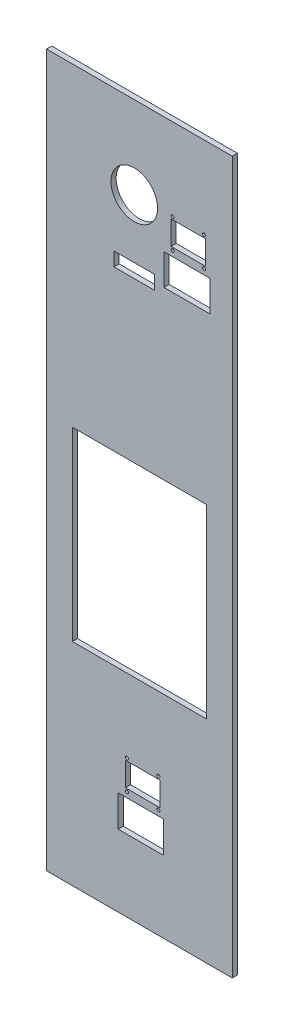
SolidWorks part; units mm, degrees
ref_plane "Plan de face" through (0, 0, 0) normal (0, 0, 1) x (1, 0, 0)
ref_plane "Plan de dessus" through (0, 0, 0) normal (0, 1, 0) x (1, 0, 0)
ref_plane "Plan de droite" through (0, 0, 0) normal (1, 0, 0) x (0, 0, -1)
sketch "Esquisse1" plane through (0, 0, 0) normal (0, 0, 1) x (1, 0, 0)
  line L1 (-90, 395) -> (90, 395)
  line L2 (-90, 395) -> (-90, -395)
  line L3 (-90, -395) -> (90, -395)
  line L4 (90, 395) -> (90, -395)
  line L5 (-90, 395) -> (90, -395) construction
  line L6 (-90, -395) -> (90, 395) construction
  point P0 (0, 0)
  dimension "D1" = 790
  dimension "D2" = 180
extrude "Boss.-Extru.1" add sketch "Esquisse1" along normal blind 5
sketch "Esquisse2" plane through (0, 0, 5) normal (0, 0, 1) x (1, 0, 0)
  line L1 (-65, 90) -> (65, 90)
  line L2 (-65, 90) -> (-65, -90)
  line L3 (-65, -90) -> (65, -90)
  line L4 (65, 90) -> (65, -90)
  line L5 (-65, 90) -> (65, -90) construction
  line L6 (-65, -90) -> (65, 90) construction
  point P0 (0, 0)
  dimension "D1" = 130
  dimension "D2" = 180
extrude "Enlèv. mat.-Extru.1" cut sketch "Esquisse2" against normal through all
sketch "Esquisse3" plane through (0, 0, 5) normal (0, 0, 1) x (1, 0, 0)
  line L0 (-90, -295) -> (90, -295)
  line L1 (-90, 395) -> (-90, -395) construction
  line L2 (90, -395) -> (90, 395) construction
  line L7 (90, -395) -> (90, 395)
  line L8 (90, 395) -> (-90, 395)
  line L9 (-90, 395) -> (-90, -395)
  line L10 (-90, -395) -> (90, -395)
  line L11 (90, -395) -> (90, -295)
  line L13 (-90, -295) -> (-90, -395)
  line L14 (-90, -395) -> (90, -395)
  dimension "D2" = 100
  dimension "D1" = 0
extrude "Enlèv. mat.-Extru.2" cut sketch "Esquisse3" against normal blind 5
sketch "Esquisse4" plane through (0, 0, 5) normal (0, 0, 1) x (1, 0, 0)
  line L0 (-5, 257.2138) -> (-5, 252.8957) construction
  line L1 (-24.6361, 258.0902) -> (14.6361, 258.0902)
  line L2 (-24.6361, 258.0902) -> (-24.6361, 244.7145)
  line L3 (-24.6361, 244.7145) -> (14.6361, 244.7145)
  line L4 (14.6361, 258.0902) -> (14.6361, 244.7145)
  line L5 (-24.6361, 258.0902) -> (14.6361, 244.7145) construction
  line L6 (-24.6361, 244.7145) -> (14.6361, 258.0902) construction
  circle A0 centre (-5, 315.0897) radius 22.5837
  point P0 (-5, 251.4023)
extrude "Enlèv. mat.-Extru.3" cut sketch "Esquisse4" against normal blind 10
sketch "Esquisse6" plane through (0, 0, 5) normal (0, 0, 1) x (1, 0, 0)
  line L1 (-20.6745, -194.84) -> (23.1088, -194.84)
  line L2 (-20.6745, -194.84) -> (-20.6745, -225.3356)
  line L3 (-20.6745, -225.3356) -> (23.1088, -225.3356)
  line L4 (23.1088, -194.84) -> (23.1088, -225.3356)
  line L5 (-13.6253, -163.9026) -> (19.9469, -163.9026)
  line L6 (-13.6253, -163.9026) -> (-13.6253, -187.0329)
  line L7 (-13.6253, -187.0329) -> (19.9469, -187.0329)
  line L8 (19.9469, -163.9026) -> (19.9469, -187.0329)
  circle A0 centre (-12.09, -189.67) radius 1.5
  circle A2 centre (18.36, -189.67) radius 1.5
  circle A3 centre (18.36, -161.27) radius 1.5
  circle A4 centre (-12.09, -161.27) radius 1.5
extrude "Enlèv. mat.-Extru.4" cut sketch "Esquisse6" against normal blind 10
sketch "Esquisse7" plane through (0, 0, 5) normal (0, 0, 1) x (1, 0, 0)
  line L1 (23.7238, 281.6024) -> (68.5123, 281.6024)
  line L2 (23.7238, 281.6024) -> (23.7238, 251.7224)
  line L3 (23.7238, 251.7224) -> (68.5123, 251.7224)
  line L4 (68.5123, 281.6024) -> (68.5123, 251.7224)
  line L5 (30.6475, 289.5839) -> (64.26, 289.5839)
  line L6 (30.6475, 289.5839) -> (30.6475, 312.695)
  line L7 (30.6475, 312.695) -> (64.26, 312.695)
  line L8 (64.26, 289.5839) -> (64.26, 312.695)
  circle A0 centre (62.66, 315.355) radius 1.5
  circle A1 centre (32.21, 315.355) radius 1.5
  circle A2 centre (32.21, 286.955) radius 1.5
  circle A3 centre (62.66, 286.955) radius 1.5
extrude "Enlèv. mat.-Extru.5" cut sketch "Esquisse7" against normal blind 10
